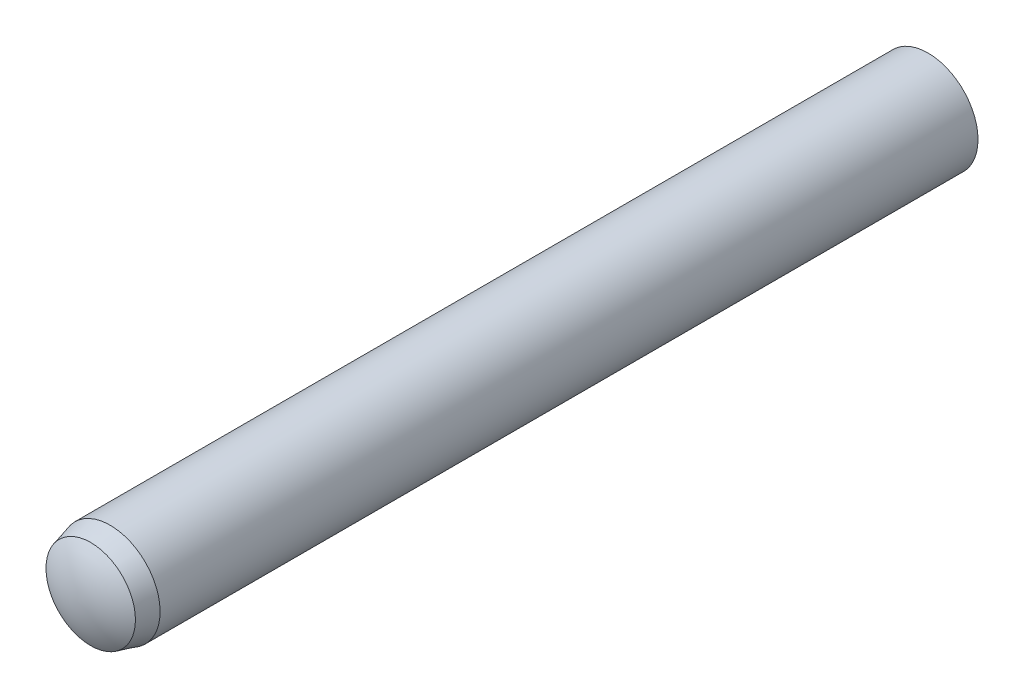
SolidWorks part; units mm, degrees
ref_plane "Front Plane" through (0, 0, 0) normal (0, 0, 1) x (1, 0, 0)
ref_plane "Top Plane" through (0, 0, 0) normal (0, 1, 0) x (1, 0, 0)
ref_plane "Right Plane" through (0, 0, 0) normal (1, 0, 0) x (0, 0, -1)
sketch "Sketch1" plane through (0, 0, 0) normal (0, 0, 1) x (1, 0, 0)
  circle A0 centre (0, 0) radius 1.5
  point P3 (0, 1.5)
  dimension "Diameter" = 3
sketch "Sketch2" plane through (0, 0, 0) normal (1, 0, 0) x (0, 0, -1)
  line L0 (-13, 0) -> (13, 0) construction
  line L1 (-13, 0) -> (-13, 1.5) construction
  line L2 (-13, 1.5) -> (13, 1.5)
  line L3 (13, 1.5) -> (13, 0) construction
  line L4 (-12.61, 1.3432) -> (-12.025, 1.5)
  arc A0 (-13, 0) -> (-12.61, 1.3432) centre (-10.4918, 0) cw
  arc A1 (13, 0) -> (12.55, 1.5) centre (10.275, 0) ccw
  point P2 (0, 0)
  point P11 (-10, 0)
  point P13 (10, 0)
  point P14 (0, 0)
  point P15 (0, 0)
  dimension "Length" = 26
  dimension "D1" = 15
  dimension "D2" = 0.45
  dimension "D3" = 0.975
  dimension "D4" = 0.585
  dimension "D5" = 3
  dimension "D6" = 3
sketch "Sketch3" plane through (0, 0, 0) normal (1, 0, 0) x (0, 0, -1)
  line L0 (-13, 0) -> (13, 0) construction
  line L1 (-12.61, 1.3432) -> (-12.025, 1.5) construction
  line L2 (-13, 0) -> (13, 0)
  line L3 (-12.61, 1.3432) -> (-12.025, 1.5)
  line L4 (-12.025, 1.5) -> (12.55, 1.5)
  arc A0 (13, 0) -> (12.55, 1.5) centre (10.275, 0) ccw construction
  arc A1 (-12.61, 1.3432) -> (-13, 0) centre (-10.4918, 0) ccw construction
  arc A2 (13, 0) -> (12.55, 1.5) centre (10.275, 0) ccw
  arc A3 (-12.61, 1.3432) -> (-13, 0) centre (-10.4918, 0) ccw
revolve "Revolve1" add sketch "Sketch3" angle 360 about L2
sketch "Sketch4" plane through (0, 0, 0) normal (1, 0, 0) x (0, 0, -1)
  point P0 (13, 0)
  point P2 (-13, 0)
equation "\"D2@Sketch2\" = \"Diameter@Sketch1\" * .15"
equation "\"D3@Sketch2\" = \"Diameter@Sketch1\" * .325"
equation "\"D4@Sketch2\" = \"D3@Sketch2\" * .6"
equation "\"D5@Sketch2\"=\"Diameter@Sketch1\""
equation "\"D6@Sketch2\"=\"D5@sketch2\""
